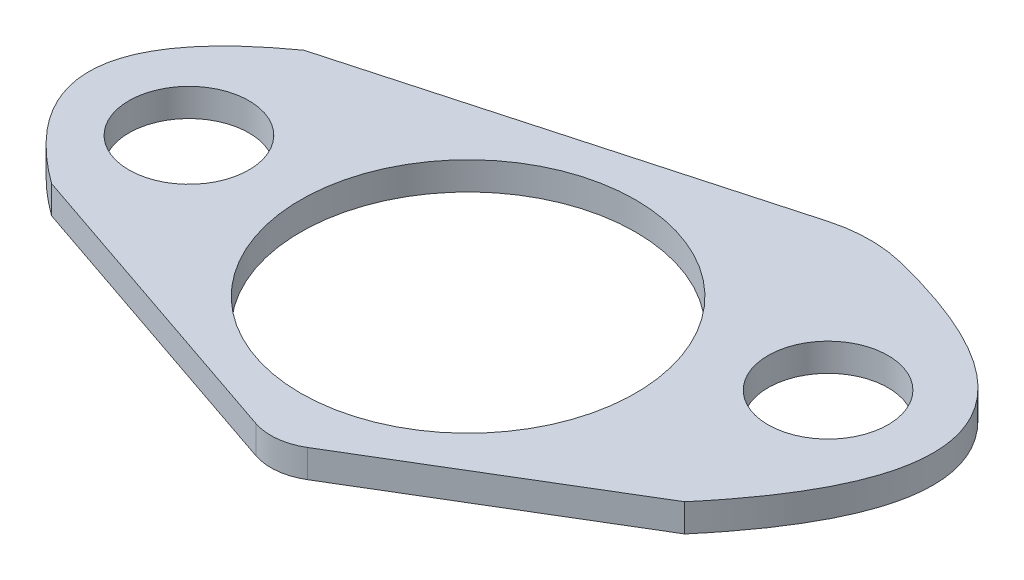
SolidWorks part; units mm, degrees
ref_plane "Front Plane" through (0, 0, 0) normal (0, 0, 1) x (1, 0, 0)
ref_plane "Top Plane" through (0, 0, 0) normal (0, 1, 0) x (1, 0, 0)
ref_plane "Right Plane" through (0, 0, 0) normal (1, 0, 0) x (0, 0, -1)
sketch "Sketch1" plane through (0, 0, 0) normal (0, 1, 0) x (1, 0, 0)
  line L0 (-10.5797, 4.6996) -> (5.3047, 9.106)
  line L2 (-10.9597, -3.9586) -> (1.0116, -8.0377)
  line L3 (1.0116, -8.0377) -> (10.2466, -2.488)
  circle A3 centre (0, 0) radius 6
  spline S0 degree 2 poles (-10.5797, 4.6996) (-16.7657, 0.2785) (-10.9597, -3.9586) knots 0 0 0 1 1 1
  spline S1 degree 2 poles (5.3047, 9.106) (17.9935, 6.6378) (10.2466, -2.488) knots 0 0 0 1 1 1
  spline S2 degree 3 poles (-0.4549, -8.015) (4.0679, -8.5153) (9.4018, -1.308) (17.9823, 1.0897) (18.9958, 5.8901) knots 0 0 0 0 0.488641 1 1 1 1 construction
  point P2 (1.3264, -8.0045)
  point P3 (1.0182, -8.0991)
  point P4 (10.2466, -2.488)
extrude "Boss-Extrude2" add sketch "Sketch1" along normal blind 1 contours L0 S1 L3 L2 S0
sketch "Sketch3" plane through (0, 1, 0) normal (0, 1, 0) x (1, 0, 0)
  circle A0 centre (0, 0) radius 6
  circle A1 centre (-10, 0) radius 2.15
  circle A2 centre (9.3515, 3.5425) radius 2.15
  dimension "D1" = 10
  dimension "D2" = 10
extrude "Cut-Extrude1" cut sketch "Sketch3" against normal blind 1
fillet "Fillet1" radius 2 1 edges at (1.0116, 0.5, 8.0377)
fillet "Fillet4" radius 5 3 edges at (5.3047, 0.5, -9.106)
